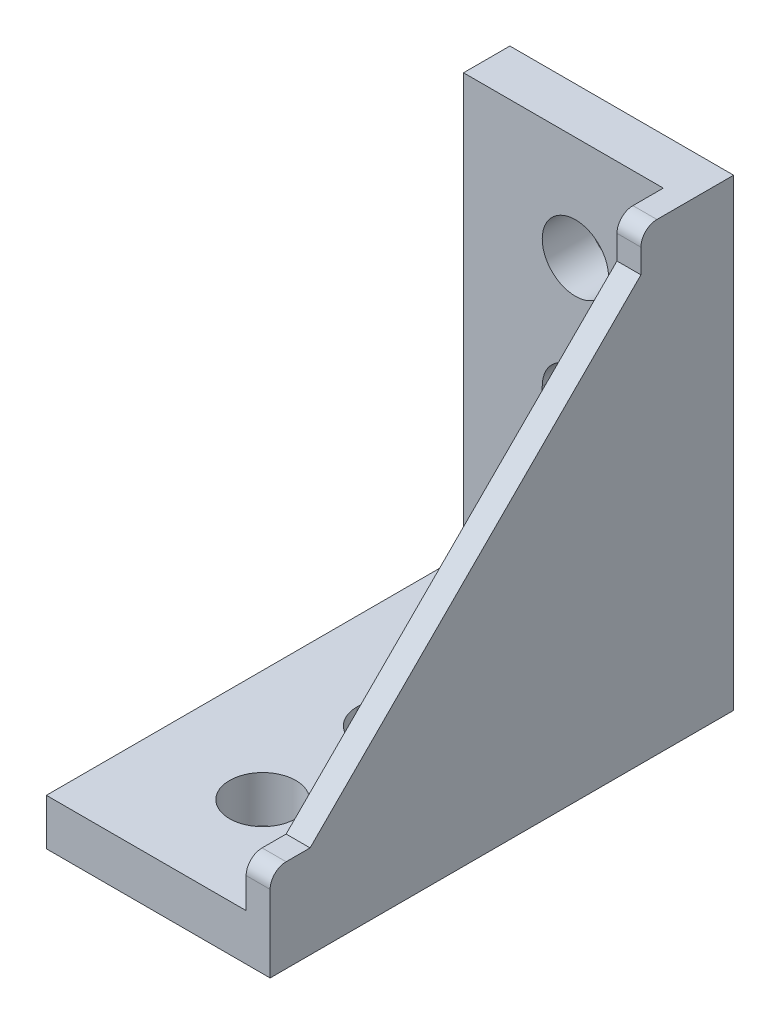
SolidWorks part; units mm, degrees
ref_plane "前视基准面" through (0, 0, 0) normal (0, 0, 1) x (1, 0, 0)
ref_plane "上视基准面" through (0, 0, 0) normal (0, 1, 0) x (1, 0, 0)
ref_plane "右视基准面" through (0, 0, 0) normal (1, 0, 0) x (0, 0, -1)
sketch "草图1" plane through (0, 0, 0) normal (0, 0, 1) x (1, 0, 0)
  line L1 (-14, 29) -> (14, 29)
  line L2 (-14, 29) -> (-14, -29)
  line L3 (-14, -29) -> (14, -29)
  line L4 (14, 29) -> (14, -29)
  line L5 (-14, 29) -> (14, -29) construction
  line L6 (-14, -29) -> (14, 29) construction
  point P0 (0, 0)
  dimension "D1" = 28
  dimension "D2" = 58
extrude "凸台-拉伸1" add sketch "草图1" along normal blind 5.8
sketch "草图2" plane through (0, 0, 0) normal (0, 0, -1) x (-1, 0, 0)
  line L0 (-14, -29) -> (-14, 29) construction
  line L1 (14, -29) -> (-14, -29)
  line L2 (14, -29) -> (14, -23.2)
  line L3 (14, -23.2) -> (-14, -23.2)
  line L4 (-14, -29) -> (-14, -23.2)
  dimension "D1" = 5.8
extrude "凸台-拉伸2" add sketch "草图2" against normal blind 58
sketch "草图3" plane through (14, 0, 0) normal (1, 0, 0) x (0, 0, -1)
  line L0 (-5.8, 29) -> (-11.6, 29)
  line L1 (-11.6, 29) -> (-11.6, 24)
  line L2 (-11.6, 24) -> (-53, -17.4)
  line L3 (-53, -17.4) -> (-58, -17.4)
  line L4 (-58, -17.4) -> (-58, -23.2)
  line L5 (-5.8, 29) -> (-5.8, -23.2)
  line L6 (-5.8, -23.2) -> (-58, -23.2)
  dimension "D1" = 5.8
  dimension "D2" = 5.8
  dimension "D3" = 5
  dimension "D4" = 5
extrude "凸台-拉伸3" add sketch "草图3" against normal blind 3
fillet "圆角1" radius 2 2 edges at (12.5, 29, 11.6) (12.5, -17.4, 58)
sketch "草图4" plane through (0, -23.2, 0) normal (0, 1, 0) x (1, 0, 0)
  line L0 (0, -17.2704) -> (0, -28.9704) construction
  line L1 (4.15, -17.2704) -> (4.15, -28.9704)
  line L2 (-4.15, -17.2704) -> (-4.15, -28.9704)
  circle A0 centre (0, -44.9294) radius 4.15
  arc A1 (4.15, -17.2704) -> (-4.15, -17.2704) centre (0, -17.2704) ccw
  arc A2 (-4.15, -28.9704) -> (4.15, -28.9704) centre (0, -28.9704) ccw
  point P5 (0, -23.1204)
  dimension "D1" = 8.3
  dimension "D2" = 4.15
  dimension "D3" = 11.7
extrude "切除-拉伸1" cut sketch "草图4" against normal through all
ref_plane "基准面1" through (0, -14.5, 14.5) normal (0, -0.7071, 0.7071) x (1, 0, 0)
mirror "镜向1" about plane through (0, -14.5, 14.5) normal (0, -0.7071, 0.7071) of "切除-拉伸1"
